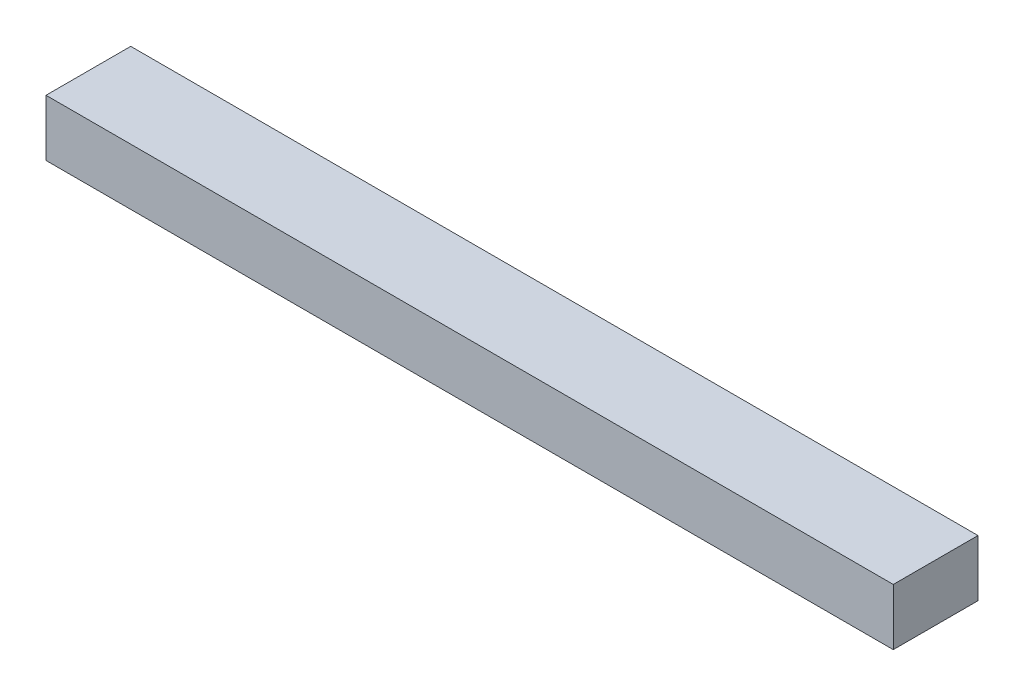
SolidWorks part; units mm, degrees
ref_plane "Front" through (0, 0, 0) normal (0, 0, 1) x (1, 0, 0)
ref_plane "Top" through (0, 0, 0) normal (0, 1, 0) x (1, 0, 0)
ref_plane "Right" through (0, 0, 0) normal (1, 0, 0) x (0, 0, -1)
sketch "Sketch1" plane through (0, 0, 0) normal (1, 0, 0) x (0, 0, -1)
  line L1 (-11.7907, 6.1765) -> (18.2093, 6.1765)
  line L2 (-11.7907, 6.1765) -> (-11.7907, -13.8235)
  line L3 (-11.7907, -13.8235) -> (18.2093, -13.8235)
  line L4 (18.2093, 6.1765) -> (18.2093, -13.8235)
  dimension "D1" = 30
  dimension "D2" = 20
extrude "Boss-Extrude1" add sketch "Sketch1" along normal blind 300
